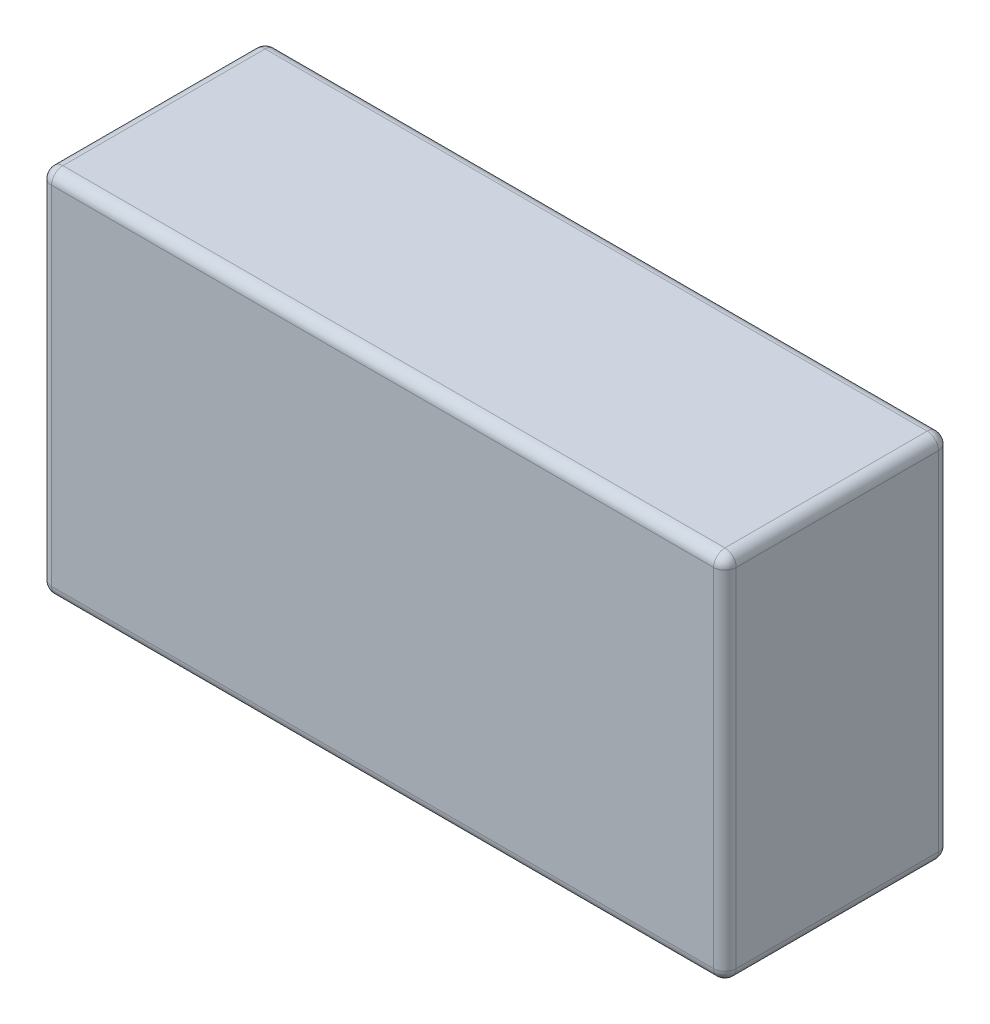
SolidWorks part; units mm, degrees
ref_plane "Front Plane" through (0, 0, 0) normal (0, 0, 1) x (1, 0, 0)
ref_plane "Top Plane" through (0, 0, 0) normal (0, 1, 0) x (1, 0, 0)
ref_plane "Right Plane" through (0, 0, 0) normal (1, 0, 0) x (0, 0, -1)
sketch "Sketch1" plane through (0, 0, 0) normal (0, 0, 1) x (1, 0, 0)
  line L1 (0, 0) -> (121.2, 0)
  line L2 (0, 0) -> (0, 65.5)
  line L3 (0, 65.5) -> (121.2, 65.5)
  line L4 (121.2, 0) -> (121.2, 65.5)
extrude "Boss-Extrude1" add sketch "Sketch1" along normal blind 39.8 contours L3 L4 L1 L2
fillet "Fillet1" radius 2 12 edges at (0, 32.75, 0) (0, 65.5, 19.9) (60.6, 65.5, 0) (121.2, 65.5, 19.9) (121.2, 32.75, 0) (0, 0, 19.9) (121.2, 0, 19.9) (60.6, 0, 0) (60.6, 65.5, 39.8) (121.2, 32.75, 39.8) (60.6, 0, 39.8) (0, 32.75, 39.8)
